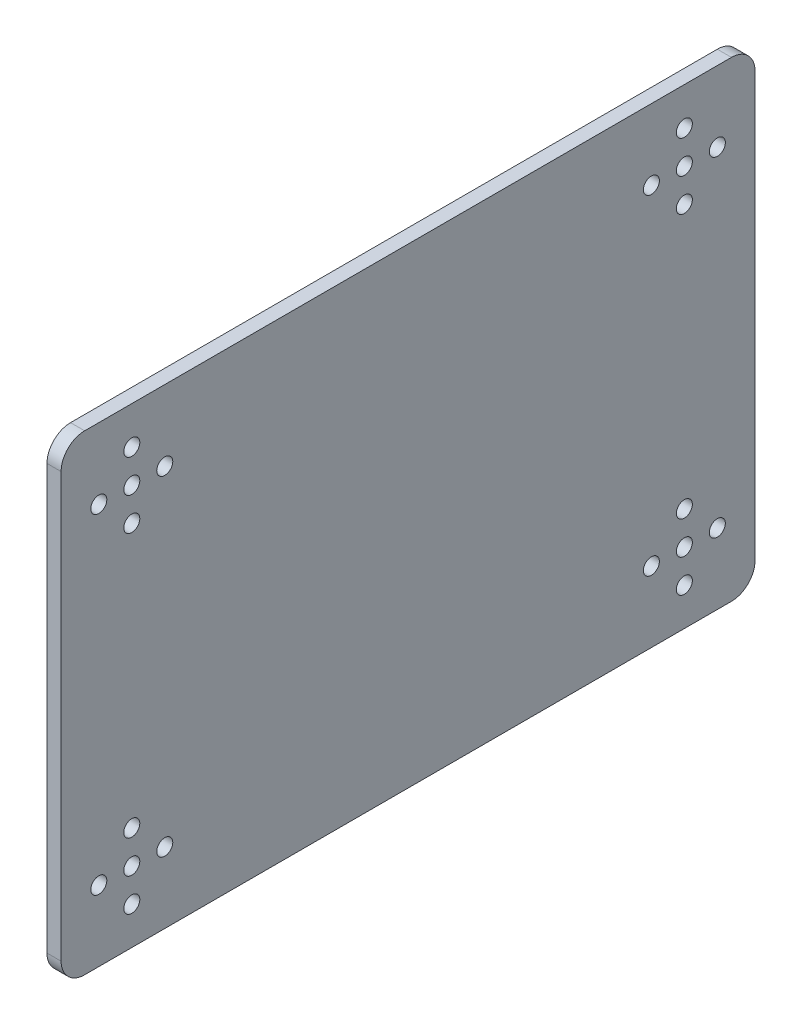
SolidWorks part; units mm, degrees
ref_plane "Front Plane" through (0, 0, 0) normal (0, 0, 1) x (1, 0, 0)
ref_plane "Top Plane" through (0, 0, 0) normal (0, 1, 0) x (1, 0, 0)
ref_plane "Right Plane" through (0, 0, 0) normal (1, 0, 0) x (0, 0, -1)
sketch "Sketch1" plane through (0, 0, 0) normal (1, 0, 0) x (0, 0, -1)
  line L1 (-73.645, -50) -> (73.645, -50)
  line L2 (-73.645, -50) -> (-73.645, 50)
  line L3 (-73.645, 50) -> (73.645, 50)
  line L4 (73.645, -50) -> (73.645, 50)
  line L5 (-73.645, -50) -> (73.645, 50) construction
  line L6 (-73.645, 50) -> (73.645, -50) construction
  point P0 (0, 0)
  dimension "D1" = 100
  dimension "D2" = 147.29
extrude "Boss-Extrude1" add sketch "Sketch1" along normal blind 3
sketch "Sketch5" plane through (3, 0, 0) normal (1, 0, 0) x (0, 0, -1)
  circle A0 centre (58.645, 35) radius 1.5
  dimension "D1" = 3
hole_wizard "M3 Clearance Hole2" positions "Sketch9" profile "Sketch10" hole size "M3" standard "ISO" end condition up to next
sketch "Sketch9" plane through (3, 0, 0) normal (1, 0, 0) x (0, 0, -1)
  point P0 (58.645, -35)
  point P3 (51.645, -35)
  point P6 (58.645, -28)
  point P9 (65.645, -35)
  point P12 (58.645, -42)
  point P15 (58.645, 35)
  point P18 (58.645, 42)
  point P21 (51.645, 35)
  point P24 (58.645, 28)
  point P27 (65.645, 35)
sketch "Sketch10" plane through (3, -35, -58.645) normal (0, 1, 0) x (0, 0, -1)
  line L0 (0, 0) -> (0, 3)
  line L1 (0, 3) -> (1.7, 3)
  line L2 (1.7, 3) -> (1.7, 0)
  line L5 (1.7, 0) -> (0, 0)
  line L11 (0, -6.35) -> (0, 107.95) construction
  dimension "Thru Hole Dia." = 3.4
  dimension "Thru Hole Depth" = 3
hole_wizard "M3 Clearance Hole3" positions "Sketch11" profile "Sketch12" hole size "M3" standard "ISO" end condition up to next
sketch "Sketch11" plane through (0, 0, 0) normal (-1, 0, 0) x (0, 0, 1)
  point P0 (58.645, 35)
  point P3 (58.645, 42)
  point P6 (65.645, 35)
  point P9 (58.645, 28)
  point P12 (51.645, 35)
  point P15 (58.645, -35)
  point P18 (58.645, -28)
  point P21 (65.645, -35)
  point P24 (58.645, -42)
  point P27 (51.645, -35)
sketch "Sketch12" plane through (0, 35, 58.645) normal (0, 1, 0) x (0, 0, 1)
  line L0 (0, 0) -> (0, 3)
  line L1 (0, 3) -> (1.7, 3)
  line L2 (1.7, 3) -> (1.7, 0)
  line L5 (1.7, 0) -> (0, 0)
  line L11 (0, -6.35) -> (0, 107.95) construction
  dimension "Thru Hole Dia." = 3.4
  dimension "Thru Hole Depth" = 3
fillet "Fillet1" radius 5 4 edges at (1.5, 50, 73.645) (1.5, -50, 73.645) (1.5, 50, -73.645) (1.5, -50, -73.645)
